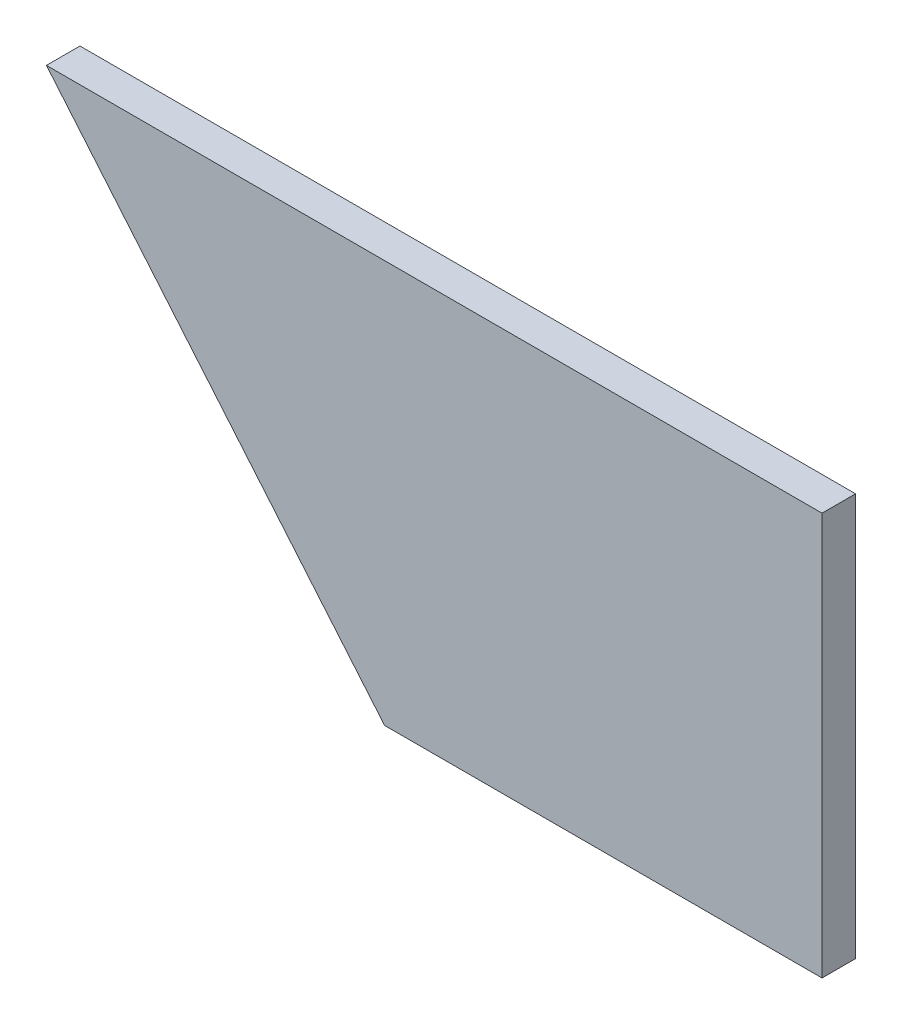
SolidWorks part; units mm, degrees
material "6061-T6 (SS)"
ref_plane "Front Plane" through (0, 0, 0) normal (0, 0, 1) x (1, 0, 0)
ref_plane "Top Plane" through (0, 0, 0) normal (0, 1, 0) x (1, 0, 0)
ref_plane "Right Plane" through (0, 0, 0) normal (1, 0, 0) x (0, 0, -1)
sketch "Sketch1" plane through (0, 0, 0) normal (0, 0, 1) x (1, 0, 0)
  line L0 (-56.9135, 0) -> (56.9135, 0) construction
  line L1 (0, -42.6271) -> (0, 42.6271) construction
  line L2 (-42.5897, 38.1) -> (42.5897, 38.1) construction
  line L3 (-16.002, -46.6212) -> (-16.002, 46.6212) construction
  line L4 (16.002, -46.8967) -> (16.002, 46.8967) construction
  line L5 (-16.002, 38.1) -> (16.002, 0) construction
  line L6 (16.002, 0) -> (12.827, 0) construction
  line L7 (-16.002, 38.1) -> (-19.177, 38.1) construction
  line L8 (-19.177, 38.1) -> (12.827, 0) construction
  line L9 (12.827, 0) -> (54.229, 0)
  line L10 (12.827, 0) -> (-19.177, 38.1)
  line L11 (-19.177, 38.1) -> (54.229, 38.1)
  line L12 (54.229, 38.1) -> (54.229, 0)
  point P4 (0, 0)
  point P8 (0, 0)
  point P11 (0, 38.1)
  point P14 (-16.002, 0)
  point P17 (16.002, 0)
  dimension "D1" = 38.1
  dimension "D2" = 16.002
  dimension "D3" = 16.002
  dimension "D4" = 3.175
  dimension "D5" = 3.175
  dimension "D6" = 41.402
extrude "Boss-Extrude1" add sketch "Sketch1" along normal blind 3.175
